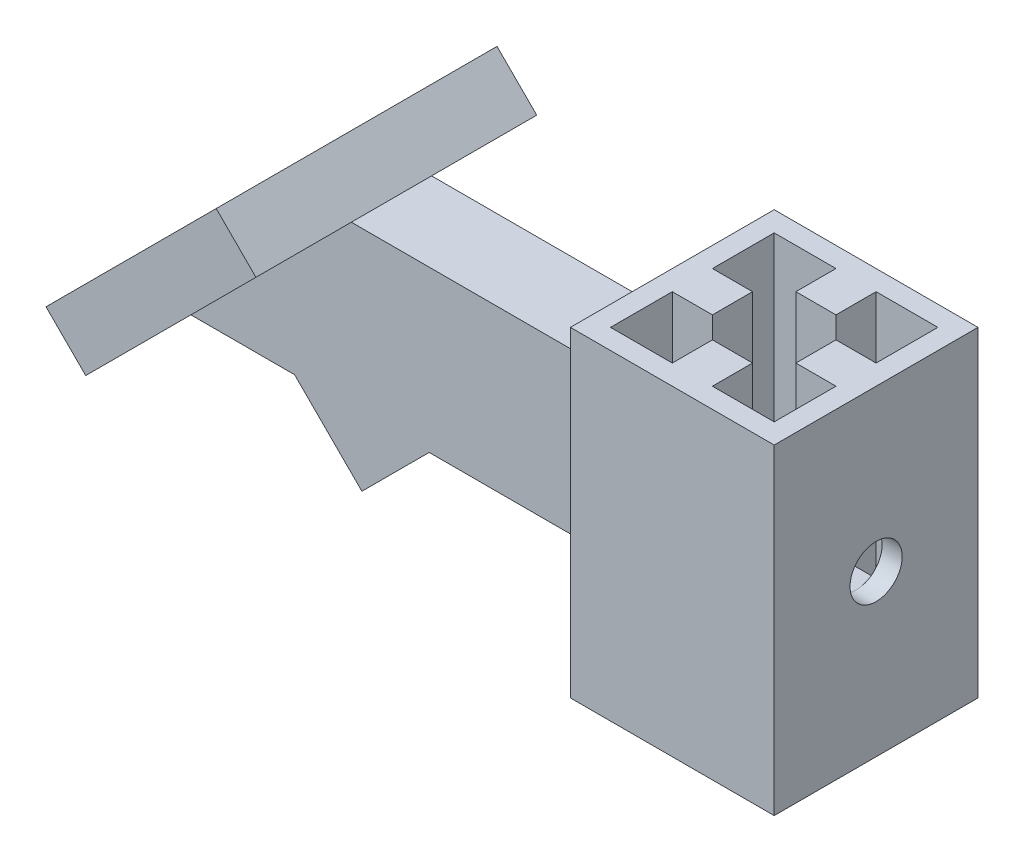
SolidWorks part; units mm, degrees
ref_plane "Alzado" through (0, 0, 0) normal (0, 0, 1) x (1, 0, 0)
ref_plane "Planta" through (0, 0, 0) normal (0, 1, 0) x (1, 0, 0)
ref_plane "Vista lateral" through (0, 0, 0) normal (1, 0, 0) x (0, 0, -1)
sketch "Croquis1" plane through (0, 0, 0) normal (0, 1, 0) x (1, 0, 0)
  line L0 (-12.7, 12.7) -> (12.7, 12.7)
  line L1 (-10.2, 10.2) -> (-2.5, 10.2)
  line L2 (-10.2, 10.2) -> (-10.2, 2.5)
  line L3 (-10.2, -10.2) -> (-2.5, -10.2)
  line L4 (10.2, 10.2) -> (10.2, 2.5)
  line L5 (-10.2, 10.2) -> (10.2, -10.2) construction
  line L6 (-10.2, -10.2) -> (10.2, 10.2) construction
  line L7 (12.7, 12.7) -> (12.7, -12.7)
  line L8 (-12.7, -12.7) -> (12.7, -12.7)
  line L9 (-12.7, 12.7) -> (-12.7, -12.7)
  line L10 (0, 12.7) -> (0, -12.7) construction
  line L11 (-12.7, 0) -> (12.7, 0) construction
  line L12 (-2.5, 10.2) -> (-2.5, 5.2)
  line L13 (-2.5, 5.2) -> (2.5, 5.2)
  line L14 (-10.2, 2.5) -> (-5.2, 2.5)
  line L15 (-5.2, 2.5) -> (-5.2, -2.5)
  line L16 (2.5, 10.2) -> (2.5, 5.2)
  line L17 (-10.2, -2.5) -> (-5.2, -2.5)
  line L18 (2.5, -10.2) -> (2.5, -5.2)
  line L19 (-2.5, -5.2) -> (2.5, -5.2)
  line L20 (-2.5, -10.2) -> (-2.5, -5.2)
  line L21 (10.2, -2.5) -> (5.2, -2.5)
  line L22 (5.2, 2.5) -> (5.2, -2.5)
  line L23 (10.2, 2.5) -> (5.2, 2.5)
  line L24 (2.5, 10.2) -> (10.2, 10.2)
  line L25 (-10.2, 10.2) -> (10.2, 10.2) construction
  line L26 (10.2, -2.5) -> (10.2, -10.2)
  line L27 (10.2, 10.2) -> (10.2, -10.2) construction
  line L28 (2.5, -10.2) -> (10.2, -10.2)
  line L29 (-10.2, -10.2) -> (10.2, -10.2) construction
  line L30 (-10.2, -2.5) -> (-10.2, -10.2)
  line L31 (-10.2, 10.2) -> (-10.2, -10.2) construction
  point P0 (0, 0)
  point P22 (0, 5.2)
  point P23 (-5.2, 0)
  dimension "D1" = 20.4
  dimension "D2" = 20.4
  dimension "D4" = 5
  dimension "D5" = 5
  dimension "D3" = 2.5
extrude "Saliente-Extruir1" add sketch "Croquis1" along normal blind 40
sketch "Croquis4" plane through (0, 0, 0) normal (0, 0, 1) x (1, 0, 0)
  line L5 (-12.7, 20) -> (-102.7, 20) construction
  line L11 (-70.7815, 11.8683) -> (-49.5683, 33.0815) construction
  line L14 (-52.0431, 35.5563) -> (-47.0934, 30.6066)
  line L16 (-73.2563, 14.3431) -> (-68.3066, 9.3934)
  line L17 (-73.2563, 14.3431) -> (-52.0431, 35.5563)
  line L18 (-68.3066, 9.3934) -> (-47.0934, 30.6066)
  line L19 (-12.7, 40) -> (-12.7, 0) construction
  line L20 (0, 40) -> (0, 59.061) construction
  line L21 (-12.7, 40) -> (12.7, 40) construction
  line L22 (0, 59.061) -> (0, -12.7567) construction
  point P13 (-70.7815, 11.8683)
  point P16 (-70.7815, 11.8683)
  point P17 (-49.5683, 33.0815)
  point P22 (-57.7, 20)
  dimension "D1" = 45
  dimension "D2" = 30
  dimension "D3" = 7
  dimension "D4" = 45
extrude "Saliente-Extruir3" add sketch "Croquis4" along normal mid plane 35 separate body
sketch "Croquis6" plane through (-12.7, 0, 0) normal (-1, 0, 0) x (0, 0, 1)
  line L0 (0, 40) -> (0, 0) construction
  line L1 (-12.7, 40) -> (12.7, 40) construction
  line L3 (-5, 30) -> (5, 30)
  line L4 (-5, 30) -> (-5, 10)
  line L5 (-5, 10) -> (5, 10)
  line L6 (5, 30) -> (5, 10)
  line L7 (-5, 30) -> (5, 10) construction
  line L8 (-5, 10) -> (5, 30) construction
  point P5 (0, 20)
  dimension "D1" = 20
  dimension "D2" = 10
extrude "Saliente-Extruir4" add sketch "Croquis6" along normal up to next
sketch "Croquis9" plane through (12.7, 0, 0) normal (1, 0, 0) x (0, 0, -1)
  line L0 (12.7, 20) -> (-12.7, 20) construction
  line L1 (12.7, 40) -> (12.7, 0) construction
  line L2 (-12.7, 40) -> (-12.7, 0) construction
  circle A0 centre (0, 20) radius 3.25
  dimension "D1" = 6.5
extrude "Cortar-Extruir3" cut sketch "Croquis9" against normal blind 10
sketch "Croquis10" plane through (12.7, 0, 0) normal (1, 0, 0) x (0, 0, -1)
  line L1 (-3.25, 23.25) -> (3.25, 23.25)
  line L2 (-3.25, 23.25) -> (-3.25, 16.75)
  line L3 (-3.25, 16.75) -> (3.25, 16.75)
  line L4 (3.25, 23.25) -> (3.25, 16.75)
  line L5 (-3.25, 23.25) -> (3.25, 16.75) construction
  line L6 (-3.25, 16.75) -> (3.25, 23.25) construction
  point P0 (0, 20)
  dimension "D1" = 6.5
  dimension "D2" = 6.5
extrude "Cortar-Extruir4" cut sketch "Croquis10" against normal blind 10 from surface at -2.5 starting at face at (10.2, 20, -5.1917)
sketch "Croquis7" plane through (-38.85, 38.85, 0) normal (0.7071, -0.7071, 0) x (0, 0, -1)
  line L0 (-17.5, -26.6579) -> (17.5, -26.6579) construction
  line L1 (-17.5, -41.6579) -> (-17.5, -11.6579) construction
  line L2 (17.5, -41.6579) -> (17.5, -11.6579) construction
  circle A0 centre (0, -26.6579) radius 3.5
  dimension "D1" = 7
extrude "Cortar-Extruir1" cut sketch "Croquis7" against normal through all both and the other way through all
sketch "Croquis11" plane through (-38.85, 38.85, 0) normal (0.7071, -0.7071, 0) x (0, 0, -1)
  line L0 (5, -40.8001) -> (5, -1.9092) construction
  line L1 (-5, -21.6579) -> (5, -21.6579)
  line L2 (-5, -21.6579) -> (-5, -31.6579)
  line L3 (-5, -31.6579) -> (5, -31.6579)
  line L4 (5, -21.6579) -> (5, -31.6579)
  line L5 (-5, -21.6579) -> (5, -31.6579) construction
  line L6 (-5, -31.6579) -> (5, -21.6579) construction
  circle A0 centre (0, -26.6579) radius 3.5
  point P0 (0, -26.6579)
  dimension "D1" = 10
extrude "Saliente-Extruir5" add sketch "Croquis11" along normal blind 21
sketch "Croquis12" plane through (0, 0, 5) normal (0, 0, 1) x (1, 0, 0)
  line L1 (-40.6289, 10) -> (-12.7, 10) construction
  line L2 (-38.0015, 10) -> (-40.6289, 10)
  line L3 (-40.6289, 10) -> (-39.3152, 8.6863)
  line L4 (-39.3152, 8.6863) -> (-38.0015, 10)
  point P5 (-38.0971, 10)
extrude "Saliente-Extruir6" add sketch "Croquis12" against normal up to vertex
